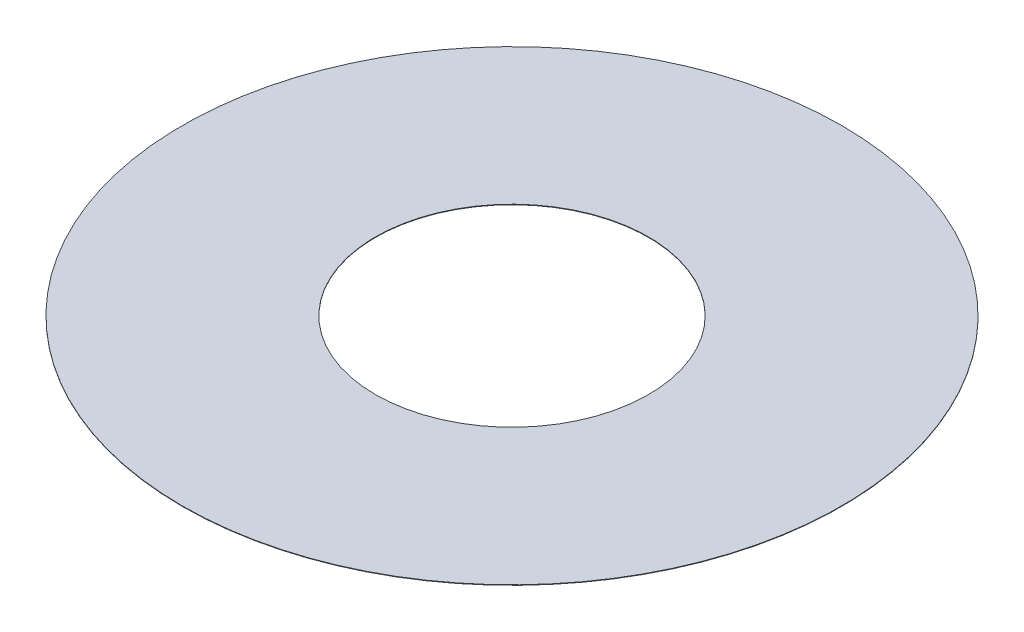
SolidWorks part; units mm, degrees
ref_plane "Ön Düzlem" through (0, 0, 0) normal (0, 0, 1) x (1, 0, 0)
ref_plane "Üst Düzlem" through (0, 0, 0) normal (0, 1, 0) x (1, 0, 0)
ref_plane "Sağ Düzlem" through (0, 0, 0) normal (1, 0, 0) x (0, 0, -1)
sketch "Sketch1" plane through (0, 0, 0) normal (0, 1, 0) x (1, 0, 0)
  circle A0 centre (0, 0) radius 152
  dimension "D1" = 304
extrude "Boss-Extrude1" add sketch "Sketch1" along normal blind 0.225
sketch "Sketch2" plane through (0, 0.225, 0) normal (0, 1, 0) x (1, 0, 0)
  circle A0 centre (0, 0) radius 63
  dimension "D1" = 126
extrude "Cut-Extrude1" cut sketch "Sketch2" against normal blind 0.225
